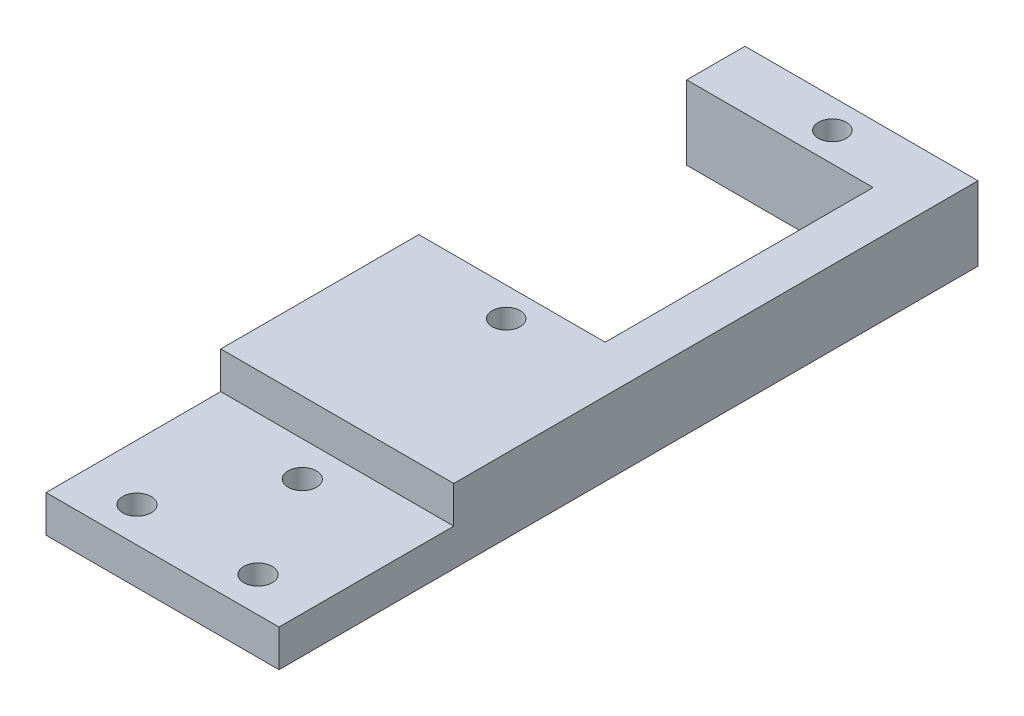
SolidWorks part; units mm, degrees
material "ABS"
ref_plane "Front" through (0, 0, 0) normal (0, 0, 1) x (1, 0, 0)
ref_plane "Top" through (0, 0, 0) normal (0, 1, 0) x (1, 0, 0)
ref_plane "Right" through (0, 0, 0) normal (1, 0, 0) x (0, 0, -1)
sketch "Sketch2" plane through (0, 0, 0) normal (0, 1, 0) x (1, 0, 0)
  line L1 (0, 0) -> (20, 0)
  line L2 (0, 0) -> (0, -60)
  line L3 (0, -60) -> (20, -60)
  line L4 (20, 0) -> (20, -60)
  dimension "D1" = 20
  dimension "D2" = 60
extrude "Boss-Extrude1" add sketch "Sketch2" along normal blind 6.35
sketch "Sketch4" plane through (0, 6.35, 0) normal (0, 1, 0) x (1, 0, 0)
  line L0 (0, 0) -> (0, -60) construction
  line L1 (0, -5) -> (16, -5)
  line L2 (0, -5) -> (0, -28)
  line L3 (0, -28) -> (16, -28)
  line L4 (16, -5) -> (16, -28)
  line L5 (20, -60) -> (20, 0) construction
  line L6 (20, 0) -> (0, 0) construction
  dimension "D1" = 4
  dimension "D2" = 5
  dimension "D3" = 23
extrude "Cut-Extrude1" cut sketch "Sketch4" against normal through all
hole_wizard "M2 Clearance Hole1" positions "Sketch8" profile "Sketch9" hole size "M2" standard "IS"
sketch "Sketch8" plane through (0, 6.35, 0) normal (0, 1, 0) x (1, 0, 0)
  line L0 (10, 0) -> (10, -60) construction
  line L1 (20, 0) -> (0, 0) construction
  line L2 (0, -60) -> (20, -60) construction
  line L3 (0, -28) -> (16, -28) construction
  point P9 (10, -2.5)
  point P11 (10, -30.5)
  point P16 (10, -31)
  dimension "D1" = 2.5
  dimension "D2" = 2.5
sketch "Sketch9" plane through (10, 6.35, 30.5) normal (1, 0, 0) x (0, 0, 1)
  line L0 (0, 0) -> (0, 5.721)
  line L1 (0, 5.721) -> (1.2, 5)
  line L2 (1.2, 5) -> (1.2, 0)
  line L5 (1.2, 0) -> (0, 0)
  line L10 (0, 5.721) -> (-1.2, 5) construction
  line L11 (0, -6.35) -> (0, 107.95) construction
  dimension "Hole Dia." = 2.4
  dimension "Hole Depth" = 5
  dimension "Drill Angle" = 118
sketch "Sketch10" plane through (20, 0, 0) normal (1, 0, 0) x (0, 0, -1)
  line L0 (-60, 6.35) -> (-60, 0) construction
  line L1 (-60, 6.35) -> (-45, 6.35)
  line L2 (-60, 6.35) -> (-60, 3.175)
  line L3 (-60, 3.175) -> (-45, 3.175)
  line L4 (-45, 6.35) -> (-45, 3.175)
  point P5 (0, 0)
  dimension "D1" = 15
extrude "Cut-Extrude2" cut sketch "Sketch10" against normal through all
sketch "Sketch12" plane through (0, 3.175, 0) normal (0, 1, 0) x (1, 0, 0)
  line L0 (10, -60) -> (10, -45) construction
  line L1 (0, -60) -> (20, -60) construction
  line L2 (0, -45) -> (20, -45) construction
  line L3 (10, -48) -> (15.1962, -57) construction
  line L4 (15.1962, -57) -> (4.8038, -57) construction
  line L5 (4.8038, -57) -> (10, -48) construction
  point P8 (10, -48.2576)
  dimension "D1" = 9
  dimension "D2" = 3
hole_wizard "#2 Clearance Hole1" positions "Sketch13" profile "Sketch14" hole size "#2" standard "ANSI Inch" end condition through all
sketch "Sketch13" plane through (0, 3.175, 0) normal (0, 1, 0) x (1, 0, 0)
  point P0 (10, -48)
  point P3 (4.8038, -57)
  point P6 (15.1962, -57)
sketch "Sketch14" plane through (10, 3.175, 48) normal (1, 0, 0) x (0, 0, 1)
  line L0 (0, 0) -> (0, 3.175)
  line L1 (0, 3.175) -> (1.2192, 3.175)
  line L2 (1.2192, 3.175) -> (1.2192, 0)
  line L5 (1.2192, 0) -> (0, 0)
  line L11 (0, -6.35) -> (0, 107.95) construction
  dimension "Thru Hole Dia." = 2.4384
  dimension "Thru Hole Depth" = 3.175
